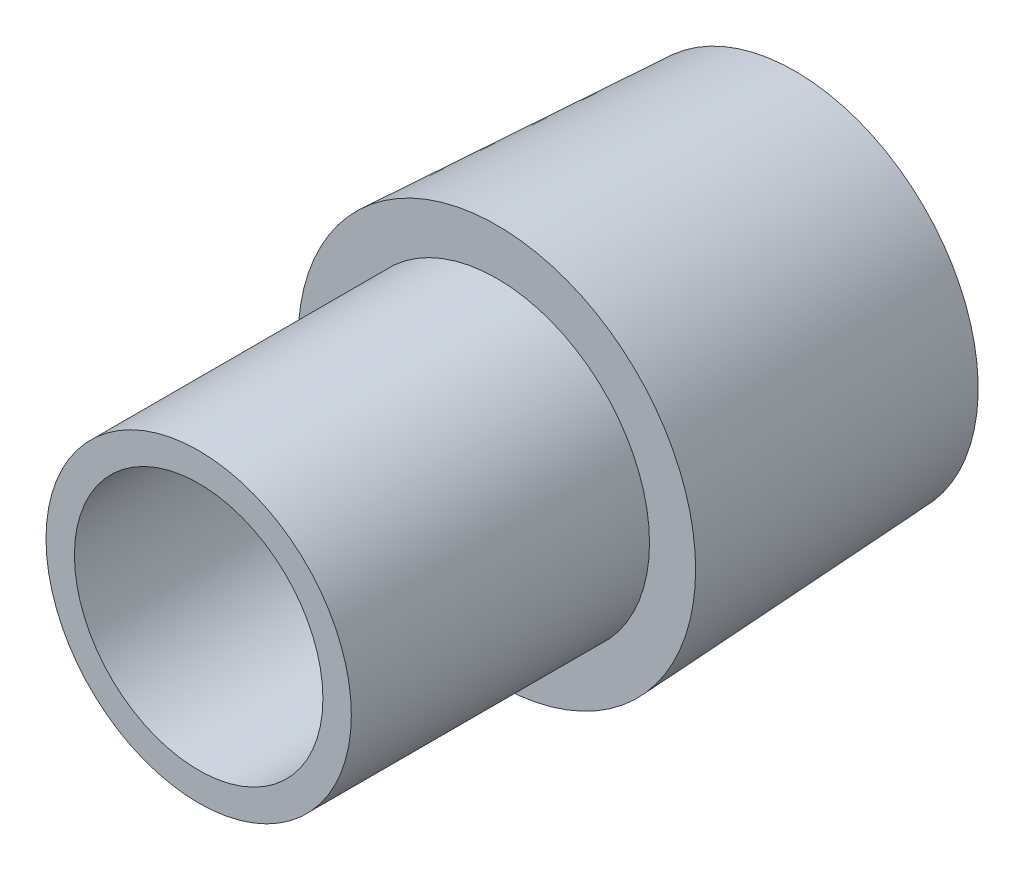
SolidWorks part; units mm, degrees
material "AISI 4130 Steel, normalized at 870C"
ref_plane "Front Plane" through (0, 0, 0) normal (0, 0, 1) x (1, 0, 0)
ref_plane "Top Plane" through (0, 0, 0) normal (0, 1, 0) x (1, 0, 0)
ref_plane "Right Plane" through (0, 0, 0) normal (1, 0, 0) x (0, 0, -1)
sketch "Sketch1" plane through (0, 0, 0) normal (0, 0, 1) x (1, 0, 0)
  circle A0 centre (0, 0) radius 6.35
  circle A1 centre (0, 0) radius 4.8768
  dimension "D1" = 12.7
  dimension "D2" = 1.4732
sketch "Sketch2" plane through (0, 0, 0) normal (0, 0, 1) x (1, 0, 0)
  circle A0 centre (0, 0) radius 4.8768 construction
  circle A1 centre (0, 0) radius 4.8768
  circle A2 centre (0, 0) radius 3.9688
  dimension "D1" = 7.9375
extrude "Boss-Extrude1" add sketch "Sketch2" along normal blind 9.525
sketch "Sketch3" plane through (0, 0, 0) normal (0, 0, -1) x (-1, 0, 0)
  circle A0 centre (0, 0) radius 6.35 construction
  circle A1 centre (0, 0) radius 6.35
  circle A2 centre (0, 0) radius 3.9688 construction
  circle A3 centre (0, 0) radius 3.9688
extrude "Boss-Extrude2" add sketch "Sketch3" along normal blind 9.525
draft "Draft1" type of draft neutral plane draft angle 3 faces to draft 1 face at (-6.35, 0, -9.525) neutral plane through (0, 0, 0) neutral plane normal (0, 0, 1) reverse direction yes parameters "D1"=3
